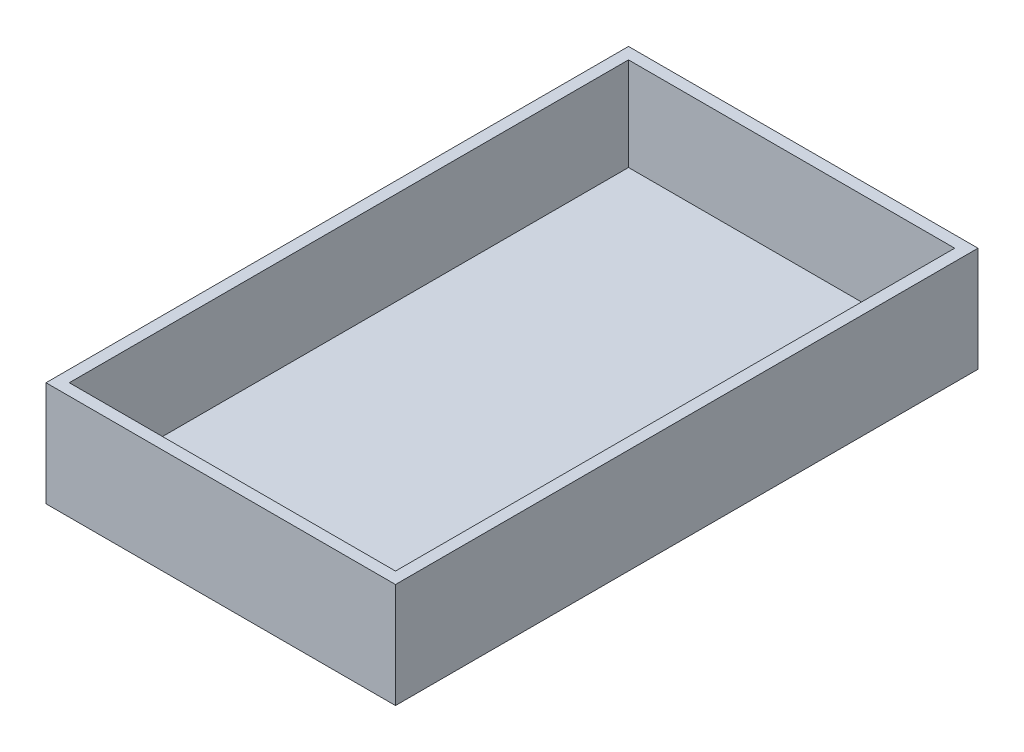
SolidWorks part; units mm, degrees
ref_plane "Front Plane" through (0, 0, 0) normal (0, 0, 1) x (1, 0, 0)
ref_plane "Top Plane" through (0, 0, 0) normal (0, 1, 0) x (1, 0, 0)
ref_plane "Right Plane" through (0, 0, 0) normal (1, 0, 0) x (0, 0, -1)
sketch "Sketch1" plane through (0, 0, 0) normal (0, 0, 1) x (1, 0, 0)
  line L1 (150, -50) -> (-150, -50)
  line L2 (150, -50) -> (150, 50)
  line L3 (150, 50) -> (-150, 50)
  line L4 (-150, -50) -> (-150, 50)
  line L5 (150, -50) -> (-150, 50) construction
  line L6 (150, 50) -> (-150, -50) construction
  point P0 (0, 0)
  dimension "D1" = 100
  dimension "D2" = 300
extrude "Boss-Extrude1" add sketch "Sketch1" along normal blind 500
shell "Shell2" thickness 10
sketch "Sketch2" plane through (0, 50, 0) normal (0, 1, 0) x (1, 0, 0)
  line L1 (150, -500) -> (-150, -500)
  line L2 (150, -500) -> (150, 0)
  line L3 (150, 0) -> (-150, 0)
  line L4 (-150, -500) -> (-150, 0)
  line L5 (150, -500) -> (-150, 0) construction
  line L6 (150, 0) -> (-150, -500) construction
  point P0 (0, -250)
  point P6 (-150, -500)
  point P8 (150, 0)
extrude "Cut-Extrude1" cut sketch "Sketch2" against normal blind 10
